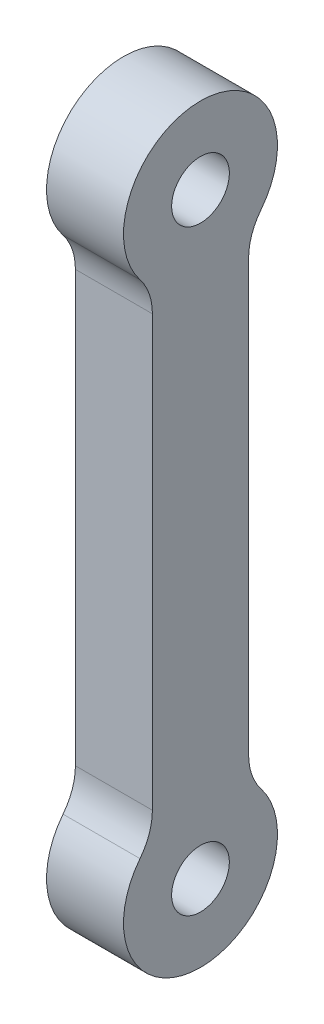
SolidWorks part; units mm, degrees
ref_plane "Front Plane" through (0, 0, 0) normal (1, 0, 0) x (0, 1, 0)
ref_plane "Top Plane" through (0, 0, 0) normal (0, 0, 1) x (0, 1, 0)
ref_plane "Right Plane" through (0, 0, 0) normal (0, 1, 0) x (-1, 0, 0)
sketch "Sketch1" plane through (0, 0, 0) normal (1, 0, 0) x (0, 1, 0)
  line L0 (15.5, 0) -> (-15.5, 0) construction
  line L1 (0, 0) -> (0, 5.1516) construction
  line L3 (11.1699, -2.5) -> (-11.1699, -2.5)
  line L5 (11.1699, 2.5) -> (-11.1699, 2.5)
  line L7 (12.3775, -2.5) -> (-12.3775, 2.5) construction
  line L8 (12.3775, 2.5) -> (-12.3775, -2.5) construction
  circle A0 centre (-15.5, 0) radius 1.5
  arc A1 (-13.0256, 3.1429) -> (-13.0256, -3.1429) centre (-15.5, 0) ccw
  arc A2 (13.0256, 3.1429) -> (13.0256, -3.1429) centre (15.5, 0) cw
  circle A3 centre (15.5, 0) radius 1.5
  arc A4 (11.1699, -2.5) -> (13.0256, -3.1429) centre (11.1699, -5.5) cw
  arc A5 (13.0256, 3.1429) -> (11.1699, 2.5) centre (11.1699, 5.5) cw
  arc A6 (-11.1699, -2.5) -> (-13.0256, -3.1429) centre (-11.1699, -5.5) ccw
  arc A7 (-11.1699, 2.5) -> (-13.0256, 3.1429) centre (-11.1699, 5.5) cw
  point P4 (0, 0)
  point P14 (0, 0)
  dimension "D2" = 8
  dimension "D3" = 3
  dimension "D5" = 3
  dimension "D1" = 31
  dimension "D4" = 5
extrude "Boss-Extrude1" add sketch "Sketch1" along normal blind 4
